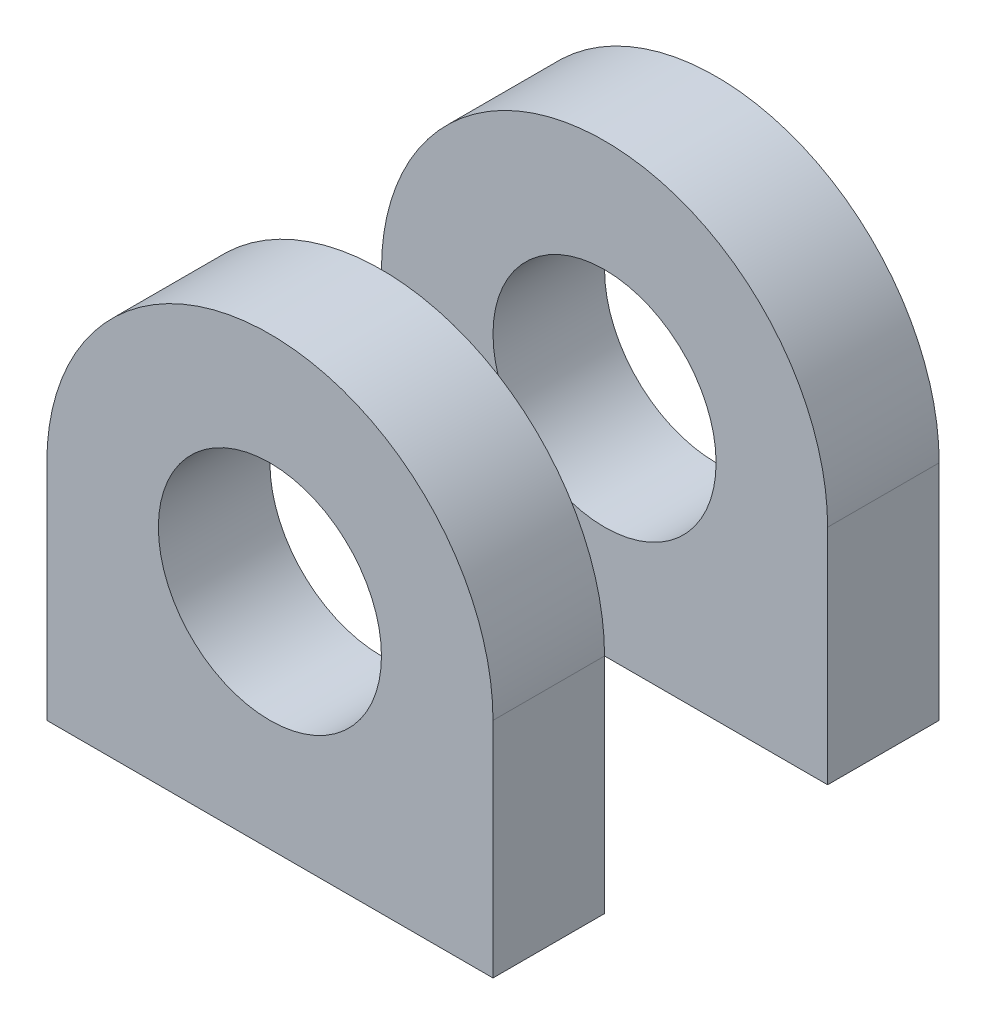
SolidWorks part; units mm, degrees
ref_plane "前视基准面" through (0, 0, 0) normal (0, 0, 1) x (1, 0, 0)
ref_plane "上视基准面" through (0, 0, 0) normal (0, 1, 0) x (1, 0, 0)
ref_plane "右视基准面" through (0, 0, 0) normal (1, 0, 0) x (0, 0, -1)
sketch "草图1" plane through (0, 0, 0) normal (0, 1, 0) x (1, 0, 0)
  line L1 (-100, -100) -> (100, -100)
  line L2 (-100, -100) -> (-100, 100)
  line L3 (-100, 100) -> (100, 100)
  line L4 (100, -100) -> (100, 100)
  line L5 (-100, -100) -> (100, 100) construction
  line L6 (-100, 100) -> (100, -100) construction
  point P0 (0, 0)
  dimension "D1" = 200
  dimension "D2" = 200
extrude "凸台-拉伸1" add sketch "草图1" along normal blind 100
sketch "草图2" plane through (0, 0, 0) normal (0, 0, 1) x (1, 0, 0)
  line L0 (-100, 100) -> (100, 100) construction
  line L1 (-100, 100) -> (100, 100)
  arc A0 (100, 100) -> (-100, 100) centre (0, 100) ccw
extrude "凸台-拉伸2" add sketch "草图2" along normal mid plane 200
sketch "草图4" plane through (0, 0, 0) normal (1, 0, 0) x (0, 0, -1)
  line L0 (-100, 0) -> (100, 0) construction
  line L1 (-50, 0) -> (50, 0)
  line L2 (-50, 0) -> (-50, 200)
  line L3 (-50, 200) -> (50, 200)
  line L4 (50, 0) -> (50, 200)
  line L5 (100, 200) -> (-100, 200) construction
  line L6 (-100, 200) -> (-100, 100) construction
  line L7 (100, 100) -> (100, 200) construction
  dimension "D1" = 50
  dimension "D2" = 50
extrude "切除-拉伸1" cut sketch "草图4" against normal through all both and the other way through all
sketch "草图5" plane through (0, 0, -100) normal (0, 0, -1) x (-1, 0, 0)
  circle A0 centre (0, 100) radius 50
  dimension "D1" = 100
extrude "切除-拉伸2" cut sketch "草图5" against normal through all both and the other way through all
sketch "草图6" plane through (0, 0, 0) normal (0, -1, 0) x (1, 0, 0)
  point P0 (0, 0)
sketch "草图7" plane through (0, 0, 0) normal (0, 0, 1) x (1, 0, 0)
  point P0 (0, 100)
